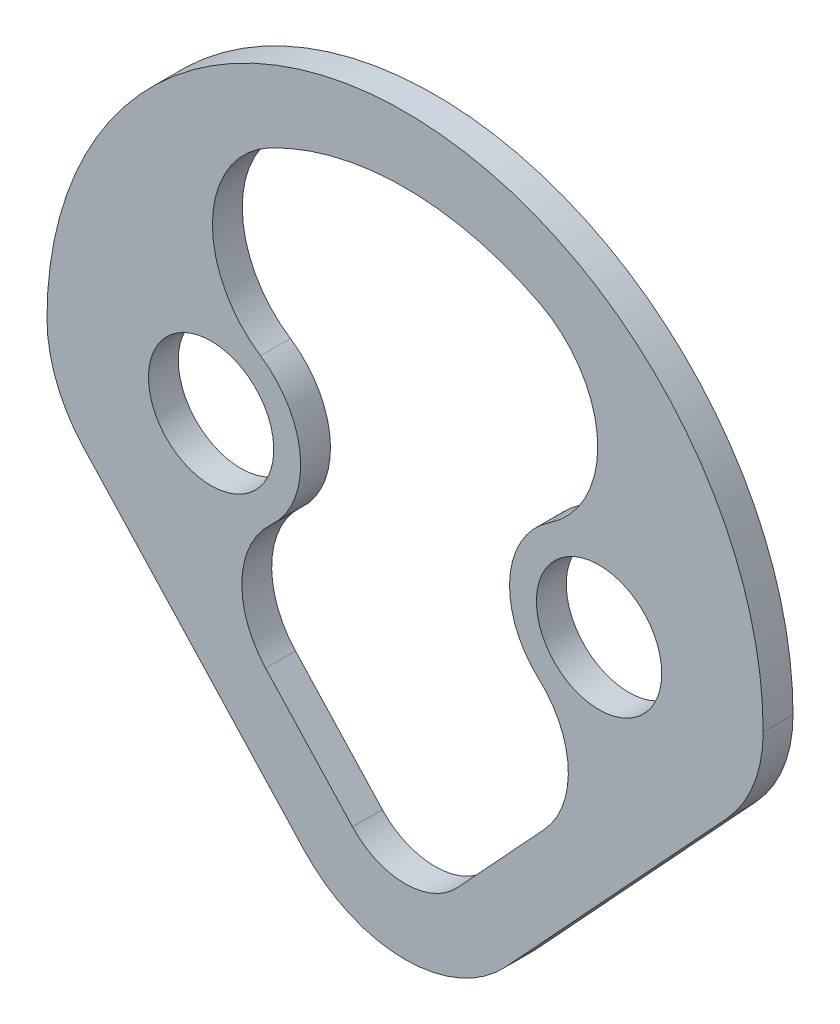
SolidWorks part; units mm, degrees
ref_plane "Front Plane" through (0, 0, 0) normal (0, 0, 1) x (1, 0, 0)
ref_plane "Top Plane" through (0, 0, 0) normal (0, 1, 0) x (1, 0, 0)
ref_plane "Right Plane" through (0, 0, 0) normal (1, 0, 0) x (0, 0, -1)
sketch "Sketch2" plane through (0, 0, 0) normal (0, 0, 1) x (1, 0, 0)
  line L0 (0, 100) -> (0, -23) construction
  line L1 (-36.5688, 40) -> (74.8335, 40) construction
  line L2 (8.8092, -8.1485) -> (23.364, 7.5865)
  line L3 (53.8843, 24.382) -> (16.8843, -15.618)
  line L4 (-53.8843, 24.382) -> (-16.8843, -15.618)
  line L5 (-8.8092, -8.1485) -> (-23.364, 7.5865)
  arc A0 (-8.8092, -8.1485) -> (8.8092, -8.1485) centre (0, 0) ccw
  arc A1 (24.2185, 52.5067) -> (22.4263, 28.886) centre (32.5, 40) ccw
  arc A2 (23.364, 7.5865) -> (22.4263, 28.886) centre (12.3525, 17.7721) ccw
  circle A3 centre (32.5, 40) radius 10.5
  arc A4 (-60, 40) -> (60, 40) centre (0, 40) cw
  arc A5 (60, 40) -> (53.8843, 24.382) centre (37, 40) cw
  arc A6 (-16.8843, -15.618) -> (16.8843, -15.618) centre (0, 0) ccw
  arc A7 (-22.5728, 83.491) -> (22.5728, 83.491) centre (0, 40) cw
  arc A8 (22.5728, 83.491) -> (24.2185, 52.5067) centre (14.2808, 67.5147) cw
  arc A9 (-22.5728, 83.491) -> (-24.2185, 52.5067) centre (-14.2808, 67.5147) ccw
  arc A10 (-60, 40) -> (-53.8843, 24.382) centre (-37, 40) ccw
  circle A11 centre (-32.5, 40) radius 10.5
  arc A12 (-23.364, 7.5865) -> (-22.4263, 28.886) centre (-12.3525, 17.7721) cw
  arc A13 (-24.2185, 52.5067) -> (-22.4263, 28.886) centre (-32.5, 40) cw
  point P7 (6.2604, 89)
  point P14 (20.2779, 48.3424)
  point P16 (0, -23)
  point P18 (-33.7986, 30.6968)
  point P27 (33.7986, 30.6968)
  dimension "D1" = 40
  dimension "D2" = 24
  dimension "D3" = 21
  dimension "D4" = 15
  dimension "D5" = 60
  dimension "D6" = 46
  dimension "D7" = 23
  dimension "D9" = 15
  dimension "D11" = 49
  dimension "D12" = 18
  dimension "D8" = 32.5
  dimension "D10" = 11
extrude "Boss-Extrude1" add sketch "Sketch2" along normal blind 5
